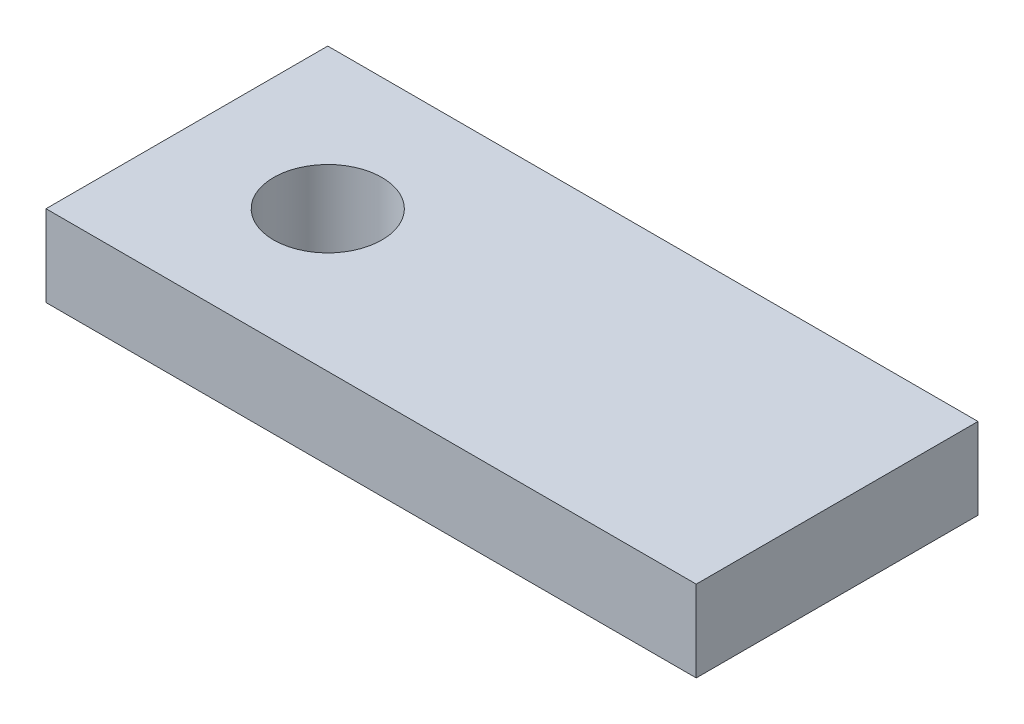
SolidWorks part; units mm, degrees
ref_plane "Front Plane" through (0, 0, 0) normal (0, 0, 1) x (1, 0, 0)
ref_plane "Top Plane" through (0, 0, 0) normal (0, 1, 0) x (1, 0, 0)
ref_plane "Right Plane" through (0, 0, 0) normal (1, 0, 0) x (0, 0, -1)
sketch "Sketch1" plane through (0, 0, 0) normal (0, 1, 0) x (1, 0, 0)
  line L1 (-2.6, 2.6) -> (9.4, 2.6)
  line L2 (-2.6, 2.6) -> (-2.6, -2.6)
  line L3 (-2.6, -2.6) -> (9.4, -2.6)
  line L4 (9.4, 2.6) -> (9.4, -2.6)
  circle A0 centre (0, 0) radius 1
  point P6 (0, 0)
  dimension "D4" = 2
  dimension "D1" = 12
  dimension "D2" = 5.2
  dimension "D3" = 2.6
  dimension "D5" = 2.6
extrude "Boss-Extrude1" add sketch "Sketch1" along normal blind 1.5
